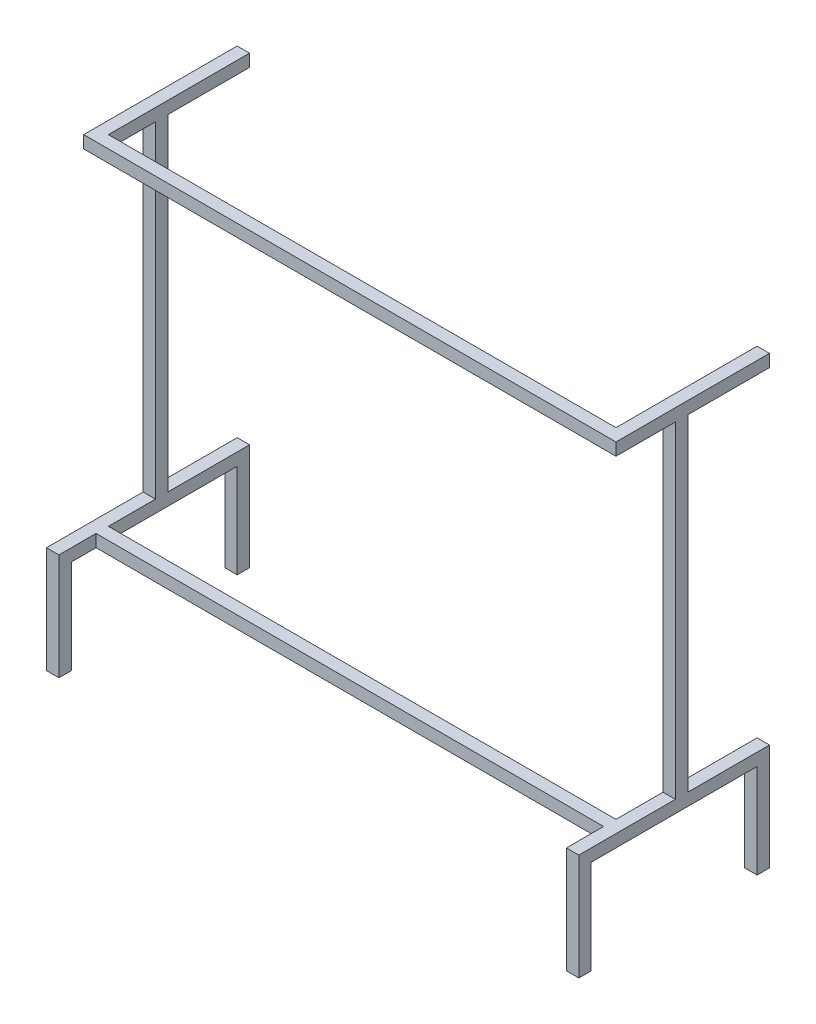
SolidWorks part; units mm, degrees
ref_plane "Front Plane" through (0, 0, 0) normal (0, 0, 1) x (1, 0, 0)
ref_plane "Top Plane" through (0, 0, 0) normal (0, 1, 0) x (1, 0, 0)
ref_plane "Right Plane" through (0, 0, 0) normal (1, 0, 0) x (0, 0, -1)
sketch "Sketch1" plane through (0, 0, 0) normal (0, 0, 1) x (1, 0, 0)
  line L0 (-537.5, 330) -> (537.5, 330)
  line L1 (-537.5, -355) -> (537.5, -355)
  line L2 (-537.5, -355) -> (-537.5, 355)
  line L3 (-537.5, 355) -> (537.5, 355)
  line L4 (537.5, -355) -> (537.5, 355)
  line L5 (-537.5, -355) -> (537.5, 355) construction
  line L6 (-537.5, 355) -> (537.5, -355) construction
  line L7 (-537.5, -330) -> (537.5, -330)
  point P0 (0, 0)
  dimension "D1" = 1075
  dimension "D2" = 710
  dimension "D3" = 25
  dimension "D4" = 25
extrude "Boss-Extrude1" add sketch "Sketch1" along normal blind 25 contours L7 L2 L1 L4 | L0 L4 L3 L2
sketch "Sketch2" plane through (0, 0, 0) normal (0, 0, -1) x (-1, 0, 0)
  line L0 (537.5, 330) -> (-537.5, 330) construction
  line L1 (-537.5, 355) -> (-512.5, 355)
  line L2 (-537.5, 355) -> (-537.5, 330)
  line L3 (-537.5, 330) -> (-512.5, 330)
  line L4 (-512.5, 355) -> (-512.5, 330)
  line L5 (537.5, 330) -> (537.5, 355) construction
  line L6 (537.5, 355) -> (512.5, 355)
  line L7 (537.5, 355) -> (537.5, 330)
  line L8 (537.5, 330) -> (512.5, 330)
  line L9 (512.5, 355) -> (512.5, 330)
  line L10 (537.5, 355) -> (-537.5, 355) construction
  line L13 (537.5, -330) -> (512.5, -330)
  line L14 (537.5, -330) -> (537.5, -355)
  line L15 (537.5, -355) -> (512.5, -355)
  line L16 (537.5, -355) -> (-537.5, -355) construction
  line L17 (512.5, -330) -> (512.5, -355)
  line L18 (-537.5, -330) -> (-512.5, -330)
  line L19 (-537.5, -330) -> (-537.5, -355)
  line L20 (-537.5, -355) -> (-512.5, -355)
  line L21 (-512.5, -330) -> (-512.5, -355)
  dimension "D1" = 25
  dimension "D2" = 25
  dimension "D3" = 25
  dimension "D4" = 25
extrude "Boss-Extrude2" add sketch "Sketch2" along normal blind 285
sketch "Sketch3" plane through (0, -330, 0) normal (0, 1, 0) x (1, 0, 0)
  line L0 (-512.5, 285) -> (-512.5, 0) construction
  line L1 (-512.5, 120) -> (-537.5, 120)
  line L2 (-512.5, 120) -> (-512.5, 95)
  line L3 (-512.5, 95) -> (-537.5, 95)
  line L4 (-537.5, 120) -> (-537.5, 95)
  line L5 (-537.5, -25) -> (-537.5, 285) construction
  line L6 (-537.5, 120) -> (537.5, 120) construction
  line L7 (537.5, -25) -> (537.5, 285) construction
  line L8 (512.5, 285) -> (512.5, 0) construction
  line L9 (537.5, 120) -> (512.5, 120)
  line L10 (537.5, 120) -> (537.5, 95)
  line L11 (537.5, 95) -> (512.5, 95)
  line L12 (512.5, 120) -> (512.5, 95)
  line L13 (-537.5, -25) -> (537.5, -25) construction
  point P16 (-525, 95)
  dimension "D1" = 25
  dimension "D2" = 25
  dimension "D3" = 120
extrude "Boss-Extrude3" add sketch "Sketch3" along normal up to next
sketch "Sketch4" plane through (0, 0, 25) normal (0, 0, 1) x (1, 0, 0)
  line L0 (-537.5, -355) -> (537.5, -355) construction
  line L1 (-537.5, -330) -> (-512.5, -330)
  line L2 (-537.5, -330) -> (-537.5, -355)
  line L3 (-537.5, -355) -> (-512.5, -355)
  line L4 (-512.5, -330) -> (-512.5, -355)
  line L6 (537.5, -330) -> (512.5, -330)
  line L7 (537.5, -330) -> (537.5, -355)
  line L8 (537.5, -355) -> (512.5, -355)
  line L9 (512.5, -330) -> (512.5, -355)
  dimension "D1" = 25
  dimension "D2" = 25
extrude "Boss-Extrude4" add sketch "Sketch4" along normal blind 75
sketch "Sketch5" plane through (0, -355, 0) normal (0, -1, 0) x (1, 0, 0)
  line L0 (-512.5, -285) -> (-512.5, 0) construction
  line L1 (-537.5, -285) -> (-512.5, -285)
  line L2 (-537.5, -285) -> (-537.5, -260)
  line L3 (-537.5, -260) -> (-512.5, -260)
  line L4 (-512.5, -285) -> (-512.5, -260)
  line L5 (-512.5, 100) -> (-512.5, 25) construction
  line L6 (-537.5, 100) -> (-512.5, 100)
  line L7 (-537.5, 100) -> (-537.5, 75)
  line L8 (-537.5, 75) -> (-512.5, 75)
  line L9 (-512.5, 100) -> (-512.5, 75)
  line L10 (537.5, 100) -> (537.5, -285) construction
  line L11 (512.5, 100) -> (537.5, 100)
  line L12 (512.5, 100) -> (512.5, 75)
  line L13 (512.5, 75) -> (537.5, 75)
  line L14 (537.5, 100) -> (537.5, 75)
  line L16 (512.5, -285) -> (537.5, -285)
  line L17 (512.5, -285) -> (512.5, -260)
  line L18 (512.5, -260) -> (537.5, -260)
  line L19 (537.5, -285) -> (537.5, -260)
  dimension "D1" = 25
  dimension "D2" = 25
  dimension "D3" = 25
  dimension "D4" = 25
extrude "Boss-Extrude5" add sketch "Sketch5" along normal blind 190
